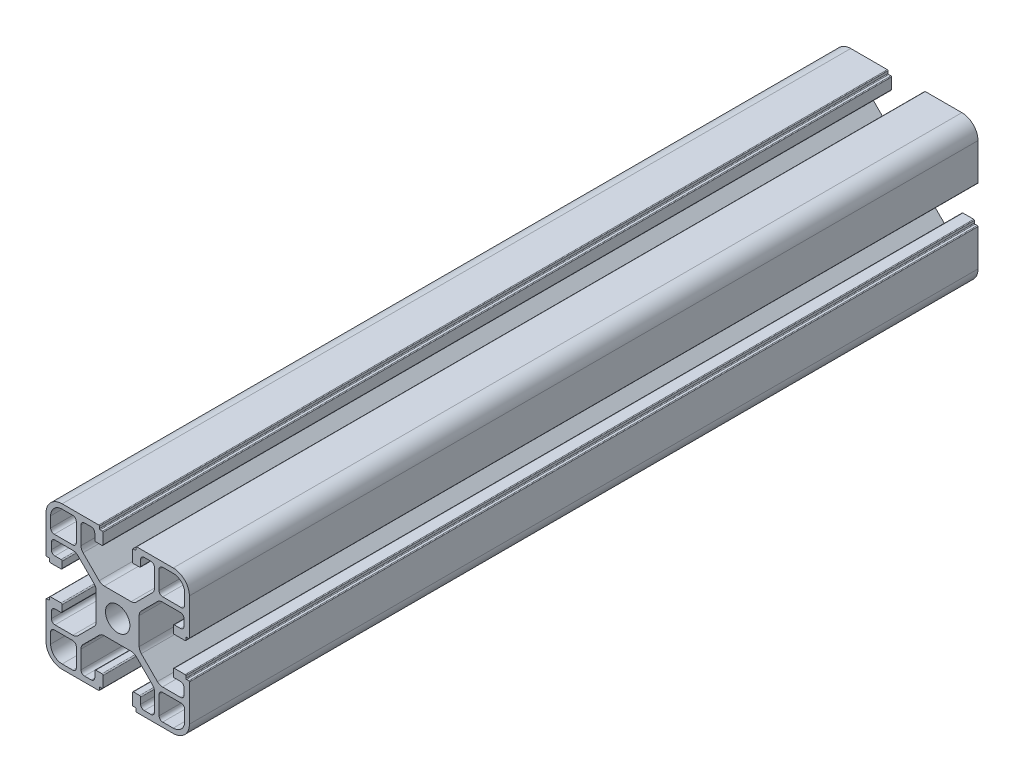
SolidWorks part; units mm, degrees
material "6063-T5"
ref_plane "Front Plane" through (0, 0, 0) normal (0, 0, 1) x (1, 0, 0)
ref_plane "Top Plane" through (0, 0, 0) normal (0, 1, 0) x (1, 0, 0)
ref_plane "Right Plane" through (0, 0, 0) normal (1, 0, 0) x (0, 0, -1)
sketch "Sketch2" plane through (0, 0, 0) normal (0, 0, 1) x (1, 0, 0)
  line L0 (4.5, 0) -> (14.7, 0)
  line L1 (40, 4.5) -> (40, 14.7)
  line L2 (35.5, 40) -> (25.3, 40)
  line L3 (0, 35.5) -> (0, 25.3)
  line L4 (15.9, 1.2) -> (15.9, 4.2)
  line L5 (24.1, 1.2) -> (24.1, 4.2)
  line L6 (38.8, 24.1) -> (35.8, 24.1)
  line L7 (35.5, 24.4) -> (35.5, 26.1)
  line L8 (14, 23.7574) -> (14, 16.2426)
  line L9 (16.2426, 14) -> (23.7574, 14)
  line L10 (26, 16.2426) -> (26, 23.7574)
  line L11 (13.4142, 14.8284) -> (8.9216, 10.3358)
  line L12 (23.7574, 26) -> (16.2426, 26)
  line L13 (4.5, 24.4) -> (4.5, 26.1)
  line L14 (1.2, 24.1) -> (4.2, 24.1)
  line L15 (15.9, 38.8) -> (15.9, 35.8)
  line L16 (14.8284, 26.5858) -> (10.3358, 31.0784)
  line L17 (13.4142, 25.1716) -> (8.9216, 29.6642)
  line L18 (14.8284, 13.4142) -> (10.3358, 8.9216)
  line L19 (25.1716, 13.4142) -> (29.6642, 8.9216)
  line L20 (26.5858, 14.8284) -> (31.0784, 10.3358)
  line L21 (26.5858, 25.1716) -> (31.0784, 29.6642)
  line L22 (25.1716, 26.5858) -> (29.6642, 31.0784)
  line L23 (24.1, 38.8) -> (24.1, 35.8)
  line L24 (14.7, 40) -> (4.5, 40)
  line L25 (25.3, 0) -> (35.5, 0)
  line L26 (38.8, 15.9) -> (35.8, 15.9)
  line L27 (40, 25.3) -> (40, 35.5)
  line L28 (1.2, 15.9) -> (4.2, 15.9)
  line L29 (0, 14.7) -> (0, 4.5)
  line L30 (4.5, 15.6) -> (4.5, 13.9)
  line L31 (35.5, 15.6) -> (35.5, 13.9)
  line L32 (15.6, 35.5) -> (13.9, 35.5)
  line L33 (24.4, 35.5) -> (26.1, 35.5)
  line L34 (15.6, 4.5) -> (13.9, 4.5)
  line L35 (24.4, 4.5) -> (26.1, 4.5)
  line L36 (12.6, 38.5) -> (10.75, 38.5)
  line L37 (1.5, 12.6) -> (1.5, 10.75)
  line L38 (27.4, 1.5) -> (29.25, 1.5)
  line L39 (38.5, 27.4) -> (38.5, 29.25)
  line L40 (38.5, 10.75) -> (38.5, 12.6)
  line L41 (29.25, 38.5) -> (27.4, 38.5)
  line L42 (1.5, 29.25) -> (1.5, 27.4)
  line L43 (10.75, 1.5) -> (12.6, 1.5)
  line L44 (35.8, 26.4) -> (37.5, 26.4)
  line L45 (35.8, 13.6) -> (37.5, 13.6)
  line L46 (4.2, 26.4) -> (2.5, 26.4)
  line L47 (13.6, 35.8) -> (13.6, 37.5)
  line L48 (26.4, 35.8) -> (26.4, 37.5)
  line L49 (4.2, 13.6) -> (2.5, 13.6)
  line L50 (13.6, 4.2) -> (13.6, 2.5)
  line L51 (26.4, 4.2) -> (26.4, 2.5)
  line L52 (9.75, 7.5074) -> (9.75, 2.5)
  line L53 (30.25, 7.5074) -> (30.25, 2.5)
  line L54 (9.75, 37.5) -> (9.75, 32.4926)
  line L55 (30.25, 37.5) -> (30.25, 32.4926)
  line L56 (32.4926, 30.25) -> (37.5, 30.25)
  line L57 (37.5, 9.75) -> (32.4926, 9.75)
  line L58 (2.5, 30.25) -> (7.5074, 30.25)
  line L59 (2.5, 9.75) -> (7.5074, 9.75)
  line L60 (31.55, 37.7) -> (31.55, 32.55)
  line L61 (32.55, 31.55) -> (37.7, 31.55)
  line L62 (1.3, 35.5) -> (1.3, 32.55)
  line L63 (4.5, 38.7) -> (7.45, 38.7)
  line L64 (32.55, 38.7) -> (35.5, 38.7)
  line L65 (38.7, 35.5) -> (38.7, 32.55)
  line L66 (8.45, 37.7) -> (8.45, 32.55)
  line L67 (2.3, 31.55) -> (7.45, 31.55)
  line L68 (1.3, 7.45) -> (1.3, 4.5)
  line L69 (2.3, 8.45) -> (7.45, 8.45)
  line L70 (8.45, 7.45) -> (8.45, 2.3)
  line L71 (4.5, 1.3) -> (7.45, 1.3)
  line L72 (31.55, 7.45) -> (31.55, 2.3)
  line L73 (32.55, 8.45) -> (37.7, 8.45)
  line L74 (38.7, 7.45) -> (38.7, 4.5)
  line L75 (32.55, 1.3) -> (35.5, 1.3)
  line L77 (14.9, 39.8) -> (14.9, 39.2)
  line L78 (15.1, 39) -> (15.7, 39)
  line L79 (25.1, 39.8) -> (25.1, 39.2)
  line L80 (24.9, 39) -> (24.3, 39)
  line L81 (25.1, 0.2) -> (25.1, 0.8)
  line L82 (24.9, 1) -> (24.3, 1)
  line L83 (14.9, 0.2) -> (14.9, 0.8)
  line L84 (15.1, 1) -> (15.7, 1)
  line L85 (0.2, 25.1) -> (0.8, 25.1)
  line L86 (1, 24.9) -> (1, 24.3)
  line L87 (0.2, 14.9) -> (0.8, 14.9)
  line L88 (1, 15.1) -> (1, 15.7)
  line L89 (39.8, 25.1) -> (39.2, 25.1)
  line L90 (39, 24.9) -> (39, 24.3)
  line L91 (39, 15.7) -> (39, 15.1)
  line L92 (39.2, 14.9) -> (39.8, 14.9)
  circle A0 centre (20, 20) radius 3.4
  arc A1 (1.3, 35.5) -> (4.5, 38.7) centre (4.5, 35.5) cw
  arc A2 (1.3, 4.5) -> (4.5, 1.3) centre (4.5, 4.5) ccw
  arc A3 (38.7, 4.5) -> (35.5, 1.3) centre (35.5, 4.5) cw
  arc A4 (35.5, 38.7) -> (38.7, 35.5) centre (35.5, 35.5) cw
  arc A5 (40, 35.5) -> (35.5, 40) centre (35.5, 35.5) ccw
  arc A6 (35.5, 0) -> (40, 4.5) centre (35.5, 4.5) ccw
  arc A7 (4.5, 0) -> (0, 4.5) centre (4.5, 4.5) cw
  arc A8 (4.5, 40) -> (0, 35.5) centre (4.5, 35.5) ccw
  arc A9 (13.4142, 14.8284) -> (14, 16.2426) centre (12, 16.2426) ccw
  arc A10 (7.5074, 9.75) -> (8.9216, 10.3358) centre (7.5074, 11.75) ccw
  arc A11 (9.75, 7.5074) -> (10.3358, 8.9216) centre (11.75, 7.5074) cw
  arc A12 (30.25, 7.5074) -> (29.6642, 8.9216) centre (28.25, 7.5074) ccw
  arc A13 (14.8284, 13.4142) -> (16.2426, 14) centre (16.2426, 12) cw
  arc A14 (25.1716, 13.4142) -> (23.7574, 14) centre (23.7574, 12) ccw
  arc A15 (32.4926, 9.75) -> (31.0784, 10.3358) centre (32.4926, 11.75) cw
  arc A16 (26.5858, 14.8284) -> (26, 16.2426) centre (28, 16.2426) cw
  arc A17 (32.4926, 30.25) -> (31.0784, 29.6642) centre (32.4926, 28.25) ccw
  arc A18 (26.5858, 25.1716) -> (26, 23.7574) centre (28, 23.7574) ccw
  arc A19 (13.4142, 25.1716) -> (14, 23.7574) centre (12, 23.7574) cw
  arc A20 (7.5074, 30.25) -> (8.9216, 29.6642) centre (7.5074, 28.25) cw
  arc A21 (9.75, 32.4926) -> (10.3358, 31.0784) centre (11.75, 32.4926) ccw
  arc A22 (30.25, 32.4926) -> (29.6642, 31.0784) centre (28.25, 32.4926) cw
  arc A23 (25.1716, 26.5858) -> (23.7574, 26) centre (23.7574, 28) cw
  arc A24 (14.8284, 26.5858) -> (16.2426, 26) centre (16.2426, 28) ccw
  arc A25 (37.7, 8.45) -> (38.7, 7.45) centre (37.7, 7.45) cw
  arc A26 (31.55, 2.3) -> (32.55, 1.3) centre (32.55, 2.3) ccw
  arc A27 (31.55, 7.45) -> (32.55, 8.45) centre (32.55, 7.45) cw
  arc A28 (8.45, 2.3) -> (7.45, 1.3) centre (7.45, 2.3) cw
  arc A29 (1.3, 7.45) -> (2.3, 8.45) centre (2.3, 7.45) cw
  arc A30 (7.45, 8.45) -> (8.45, 7.45) centre (7.45, 7.45) cw
  arc A31 (38.7, 32.55) -> (37.7, 31.55) centre (37.7, 32.55) cw
  arc A32 (31.55, 32.55) -> (32.55, 31.55) centre (32.55, 32.55) ccw
  arc A33 (31.55, 37.7) -> (32.55, 38.7) centre (32.55, 37.7) cw
  arc A34 (7.45, 38.7) -> (8.45, 37.7) centre (7.45, 37.7) cw
  arc A35 (8.45, 32.55) -> (7.45, 31.55) centre (7.45, 32.55) cw
  arc A36 (1.3, 32.55) -> (2.3, 31.55) centre (2.3, 32.55) ccw
  arc A37 (30.25, 2.5) -> (29.25, 1.5) centre (29.25, 2.5) cw
  arc A38 (26.4, 2.5) -> (27.4, 1.5) centre (27.4, 2.5) ccw
  arc A39 (13.6, 2.5) -> (12.6, 1.5) centre (12.6, 2.5) cw
  arc A40 (9.75, 2.5) -> (10.75, 1.5) centre (10.75, 2.5) ccw
  arc A41 (26.4, 37.5) -> (27.4, 38.5) centre (27.4, 37.5) cw
  arc A42 (30.25, 37.5) -> (29.25, 38.5) centre (29.25, 37.5) ccw
  arc A43 (37.5, 26.4) -> (38.5, 27.4) centre (37.5, 27.4) ccw
  arc A44 (37.5, 30.25) -> (38.5, 29.25) centre (37.5, 29.25) cw
  arc A45 (37.5, 13.6) -> (38.5, 12.6) centre (37.5, 12.6) cw
  arc A46 (37.5, 9.75) -> (38.5, 10.75) centre (37.5, 10.75) ccw
  arc A47 (2.5, 9.75) -> (1.5, 10.75) centre (2.5, 10.75) cw
  arc A48 (2.5, 13.6) -> (1.5, 12.6) centre (2.5, 12.6) ccw
  arc A49 (2.5, 26.4) -> (1.5, 27.4) centre (2.5, 27.4) cw
  arc A50 (2.5, 30.25) -> (1.5, 29.25) centre (2.5, 29.25) ccw
  arc A51 (9.75, 37.5) -> (10.75, 38.5) centre (10.75, 37.5) cw
  arc A52 (13.6, 37.5) -> (12.6, 38.5) centre (12.6, 37.5) ccw
  arc A53 (26.1, 35.5) -> (26.4, 35.8) centre (26.1, 35.8) ccw
  arc A54 (24.1, 35.8) -> (24.4, 35.5) centre (24.4, 35.8) ccw
  arc A55 (15.9, 35.8) -> (15.6, 35.5) centre (15.6, 35.8) cw
  arc A56 (13.9, 35.5) -> (13.6, 35.8) centre (13.9, 35.8) cw
  arc A57 (13.9, 4.5) -> (13.6, 4.2) centre (13.9, 4.2) ccw
  arc A58 (15.9, 4.2) -> (15.6, 4.5) centre (15.6, 4.2) ccw
  arc A59 (24.1, 4.2) -> (24.4, 4.5) centre (24.4, 4.2) cw
  arc A60 (26.1, 4.5) -> (26.4, 4.2) centre (26.1, 4.2) cw
  arc A61 (35.5, 13.9) -> (35.8, 13.6) centre (35.8, 13.9) ccw
  arc A62 (35.8, 15.9) -> (35.5, 15.6) centre (35.8, 15.6) ccw
  arc A63 (35.8, 24.1) -> (35.5, 24.4) centre (35.8, 24.4) cw
  arc A64 (35.5, 26.1) -> (35.8, 26.4) centre (35.8, 26.1) cw
  arc A65 (4.5, 13.9) -> (4.2, 13.6) centre (4.2, 13.9) cw
  arc A66 (4.2, 15.9) -> (4.5, 15.6) centre (4.2, 15.6) cw
  arc A67 (4.2, 24.1) -> (4.5, 24.4) centre (4.2, 24.4) ccw
  arc A68 (4.5, 26.1) -> (4.2, 26.4) centre (4.2, 26.1) ccw
  arc A69 (25.3, 0) -> (25.1, 0.2) centre (25.3, 0.2) cw
  arc A70 (25.1, 0.8) -> (24.9, 1) centre (24.9, 0.8) ccw
  arc A71 (24.3, 1) -> (24.1, 1.2) centre (24.3, 1.2) cw
  arc A72 (14.7, 0) -> (14.9, 0.2) centre (14.7, 0.2) ccw
  arc A73 (14.9, 0.8) -> (15.1, 1) centre (15.1, 0.8) cw
  arc A74 (15.7, 1) -> (15.9, 1.2) centre (15.7, 1.2) ccw
  arc A75 (39.8, 14.9) -> (40, 14.7) centre (39.8, 14.7) cw
  arc A76 (39, 15.1) -> (39.2, 14.9) centre (39.2, 15.1) ccw
  arc A77 (38.8, 15.9) -> (39, 15.7) centre (38.8, 15.7) cw
  arc A78 (0, 25.3) -> (0.2, 25.1) centre (0.2, 25.3) ccw
  arc A79 (0.8, 25.1) -> (1, 24.9) centre (0.8, 24.9) cw
  arc A80 (1, 24.3) -> (1.2, 24.1) centre (1.2, 24.3) ccw
  arc A81 (0, 14.7) -> (0.2, 14.9) centre (0.2, 14.7) cw
  arc A82 (0.8, 14.9) -> (1, 15.1) centre (0.8, 15.1) ccw
  arc A83 (1, 15.7) -> (1.2, 15.9) centre (1.2, 15.7) cw
  arc A84 (39, 24.3) -> (38.8, 24.1) centre (38.8, 24.3) cw
  arc A85 (39.2, 25.1) -> (39, 24.9) centre (39.2, 24.9) ccw
  arc A86 (40, 25.3) -> (39.8, 25.1) centre (39.8, 25.3) cw
  arc A87 (24.3, 39) -> (24.1, 38.8) centre (24.3, 38.8) ccw
  arc A88 (25.1, 39.2) -> (24.9, 39) centre (24.9, 39.2) cw
  arc A89 (25.3, 40) -> (25.1, 39.8) centre (25.3, 39.8) ccw
  arc A90 (14.9, 39.2) -> (15.1, 39) centre (15.1, 39.2) ccw
  arc A91 (15.7, 39) -> (15.9, 38.8) centre (15.7, 38.8) cw
  arc A92 (14.7, 40) -> (14.9, 39.8) centre (14.7, 39.8) cw
  point P93 (0, 0)
extrude "Boss-Extrude1" add sketch "Sketch2" along normal blind 220
sketch "Szkic1" plane through (0, 40, 0) normal (0, 1, 0) x (1, 0, 0)
  line L0 (40, -110) -> (0, -110) construction
  line L1 (40, -220) -> (40, 0) construction
  line L2 (0, -220) -> (0, 0) construction
  circle A0 centre (20, -110) radius 4
  dimension "D1" = 8
extrude "Wytnij-wyciągnięcie1" cut sketch "Szkic1" against normal through all both and the other way through all
